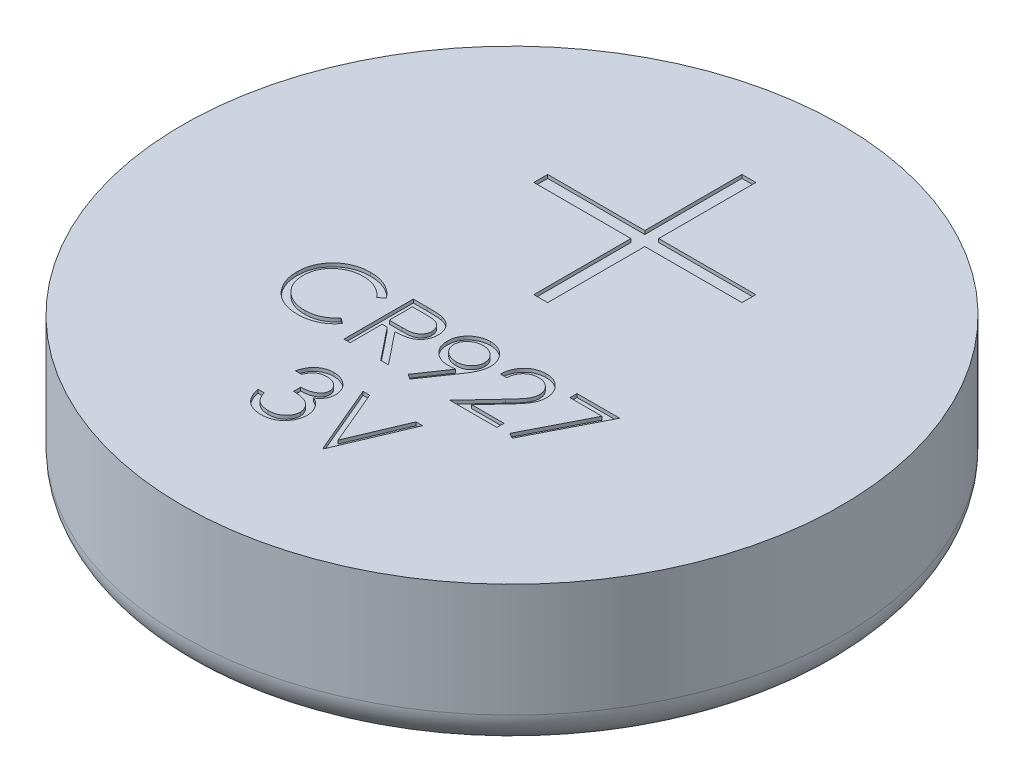
SolidWorks part; units mm, degrees
material "Zinc AC43A (Zn-4Al-2.5Cu-0.04Mg; Number 2 Die Casting Alloy; Zamak 2), Die Cast"
ref_plane "Front Plane" through (0, 0, 0) normal (0, 0, 1) x (1, 0, 0)
ref_plane "Top Plane" through (0, 0, 0) normal (0, 1, 0) x (1, 0, 0)
ref_plane "Right Plane" through (0, 0, 0) normal (1, 0, 0) x (0, 0, -1)
sketch "Sketch1" plane through (0, 0, 0) normal (0, 1, 0) x (1, 0, 0)
  circle A0 centre (0, 0) radius 4.75
  dimension "D1" = 9.5
extrude "Boss-Extrude1" add sketch "Sketch1" along normal blind 2.7
sketch "Sketch2" plane through (0, 0, 0) normal (0, -1, 0) x (1, 0, 0)
  circle A0 centre (0, 0) radius 3.6449
  circle A1 centre (0, 0) radius 4.75 construction
  circle A2 centre (0, 0) radius 4.75
  dimension "D1" = 7.2898
extrude "Cut-Extrude1" cut sketch "Sketch2" against normal offset from surface (0.5664 mm away) 2.1336 up to face at (0, 2.7, 4.75)
fillet "Fillet1" radius 0.5 1 edges at (0, 0.5664, 4.75)
fillet "Fillet2" radius 0.2 1 edges at (0, 0, -3.6449)
sketch "Sketch3" plane through (0, 0.5664, 0) normal (0, -1, 0) x (1, 0, 0)
  circle A0 centre (0, 0) radius 3.6449 construction
  circle A1 centre (0, 0) radius 3.6449
  circle A2 centre (0, 0) radius 4.25 construction
  circle A3 centre (0, 0) radius 4.25
extrude "Cut-Extrude2" cut sketch "Sketch3" against normal blind 0.15
sketch "Sketch5" plane through (0, 2.7, 0) normal (0, 1, 0) x (1, 0, 0)
  text T0 "\r\nCR927\r\n" font "Century Gothic" height 1
  text T1 "3V" font "Century Gothic" height 1
extrude "Cut-Extrude4" cut sketch "Sketch5" against normal blind 0.05
sketch "Sketch6" plane through (0, 2.7, 0) normal (0, 1, 0) x (1, 0, 0)
  line L0 (0, 0) -> (0, 1.9144) construction
  line L1 (-0.1, 0.4144) -> (0.1, 0.4144)
  line L2 (-0.1, 0.4144) -> (-0.1, 3.4144)
  line L3 (-0.1, 3.4144) -> (0.1, 3.4144)
  line L4 (0.1, 0.4144) -> (0.1, 3.4144)
  line L5 (-0.1, 0.4144) -> (0.1, 3.4144) construction
  line L6 (-0.1, 3.4144) -> (0.1, 0.4144) construction
  line L7 (-1.5, 1.8144) -> (1.5, 1.8144)
  line L8 (-1.5, 1.8144) -> (-1.5, 2.0144)
  line L9 (-1.5, 2.0144) -> (1.5, 2.0144)
  line L10 (1.5, 1.8144) -> (1.5, 2.0144)
  line L11 (-1.5, 1.8144) -> (1.5, 2.0144) construction
  line L12 (-1.5, 2.0144) -> (1.5, 1.8144) construction
  point P0 (0, 1.9144)
  point P5 (0, 1.9144)
  dimension "D1" = 3
  dimension "D2" = 0.2
extrude "Cut-Extrude5" cut sketch "Sketch6" against normal blind 0.05 contours L7 L10 L9 L4 | L9 L2 L7 L4 | L7 L2 L1 L4 | L9 L8 L7 L2 | L2 L9 L4 L3
